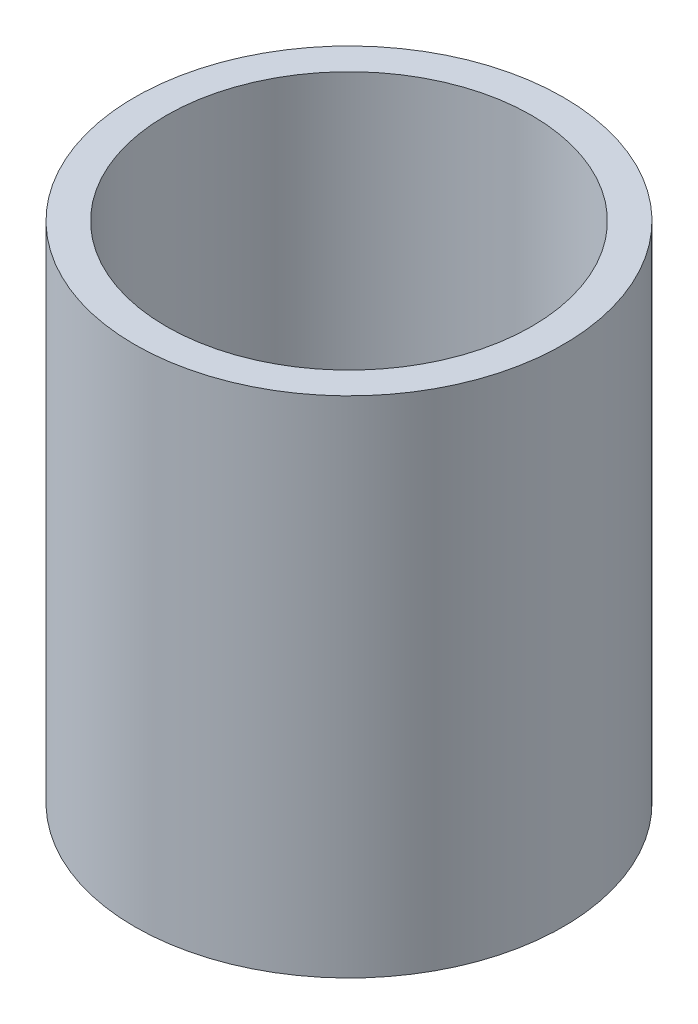
SolidWorks part; units mm, degrees
ref_plane "Front Plane" through (0, 0, 0) normal (0, 0, 1) x (1, 0, 0)
ref_plane "Top Plane" through (0, 0, 0) normal (0, 1, 0) x (1, 0, 0)
ref_plane "Right Plane" through (0, 0, 0) normal (1, 0, 0) x (0, 0, -1)
sketch "Sketch1" plane through (0, 0, 0) normal (0, 1, 0) x (1, 0, 0)
  circle A0 centre (0, 0) radius 36.83
  circle A1 centre (0, 0) radius 43.18
  dimension "D1" = 86.36
  dimension "D2" = 73.66
extrude "Boss-Extrude1" add sketch "Sketch1" along normal blind 101.6
